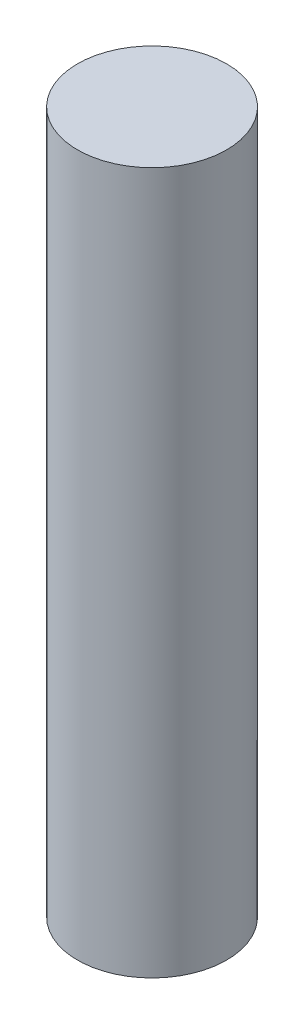
SolidWorks part; units mm, degrees
ref_plane "Front Plane" through (0, 0, 0) normal (0, 0, 1) x (1, 0, 0)
ref_plane "Top Plane" through (0, 0, 0) normal (0, 1, 0) x (1, 0, 0)
ref_plane "Right Plane" through (0, 0, 0) normal (1, 0, 0) x (0, 0, -1)
sketch "Sketch1" plane through (0, 0, 0) normal (0, 1, 0) x (1, 0, 0)
  circle A0 centre (0, 0) radius 2.54
  dimension "D1" = 5.08
extrude "Boss-Extrude1" add sketch "Sketch1" along normal blind 23.9
ref_plane "Plane1" through (0, 11.95, 0) normal (0, -1, 0) x (-1, 0, 0)
